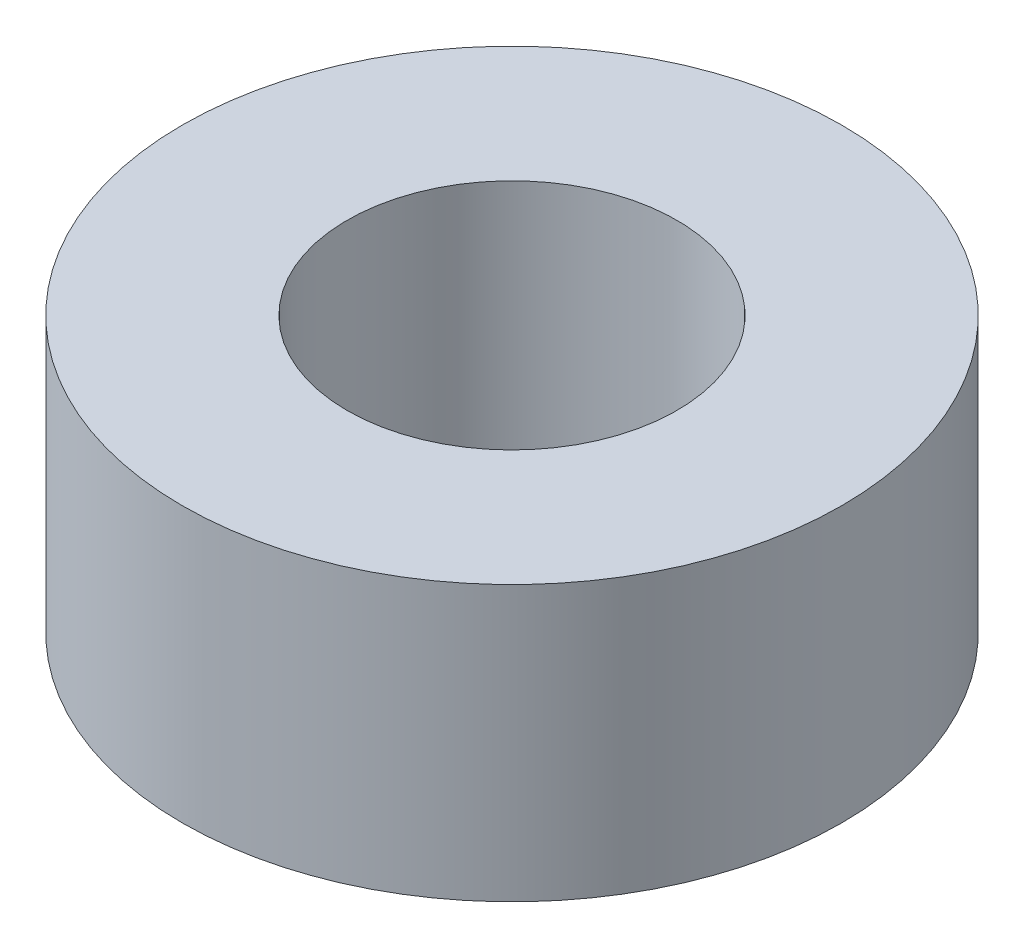
SolidWorks part; units mm, degrees
ref_plane "Front Plane" through (0, 0, 0) normal (0, 0, 1) x (1, 0, 0)
ref_plane "Top Plane" through (0, 0, 0) normal (0, 1, 0) x (1, 0, 0)
ref_plane "Right Plane" through (0, 0, 0) normal (1, 0, 0) x (0, 0, -1)
sketch "Sketch1" plane through (0, 0, 0) normal (0, 1, 0) x (1, 0, 0)
  circle A0 centre (0, 0) radius 3
  circle A1 centre (0, 0) radius 1.5
  dimension "D1" = 6
  dimension "D2" = 3
extrude "Boss-Extrude1" add sketch "Sketch1" along normal blind 2.5
